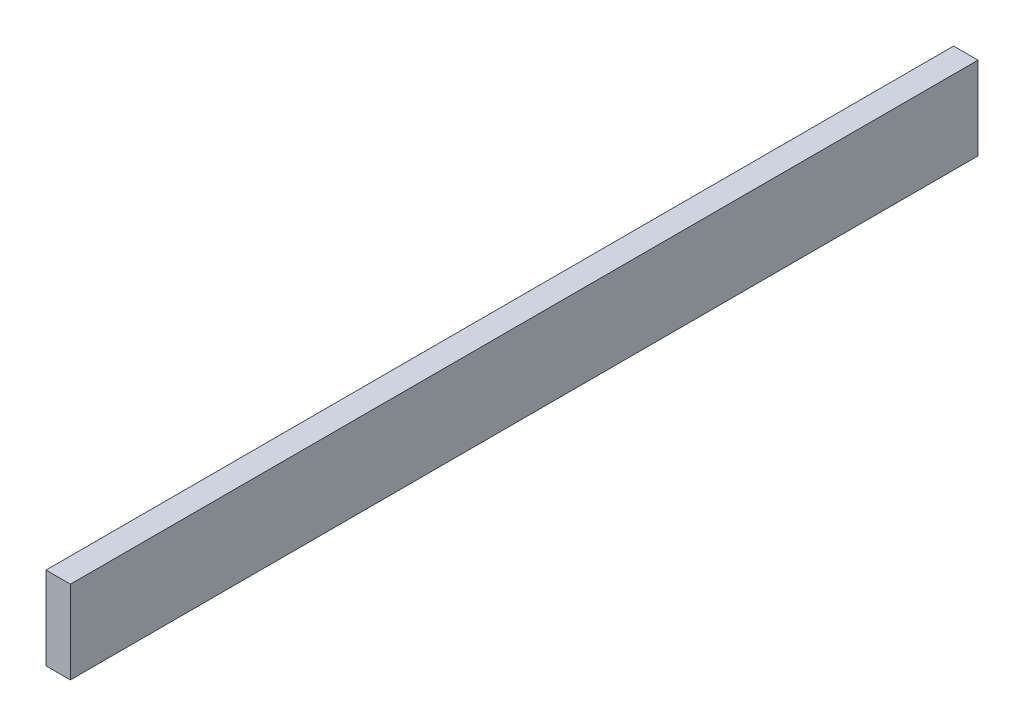
SolidWorks part; units mm, degrees
ref_plane "Front" through (0, 0, 0) normal (0, 0, 1) x (1, 0, 0)
ref_plane "Top" through (0, 0, 0) normal (0, 1, 0) x (1, 0, 0)
ref_plane "Right" through (0, 0, 0) normal (1, 0, 0) x (0, 0, -1)
sketch "Skizze1" plane through (0, 0, 0) normal (1, 0, 0) x (0, 0, -1)
  line L1 (0, 0) -> (186, 0)
  line L2 (0, 0) -> (0, 17)
  line L3 (0, 17) -> (186, 17)
  line L4 (186, 0) -> (186, 17)
  dimension "D1" = 17
  dimension "D2" = 186
extrude "Aufsatz-Linear austragen1" add sketch "Skizze1" along normal blind 5
